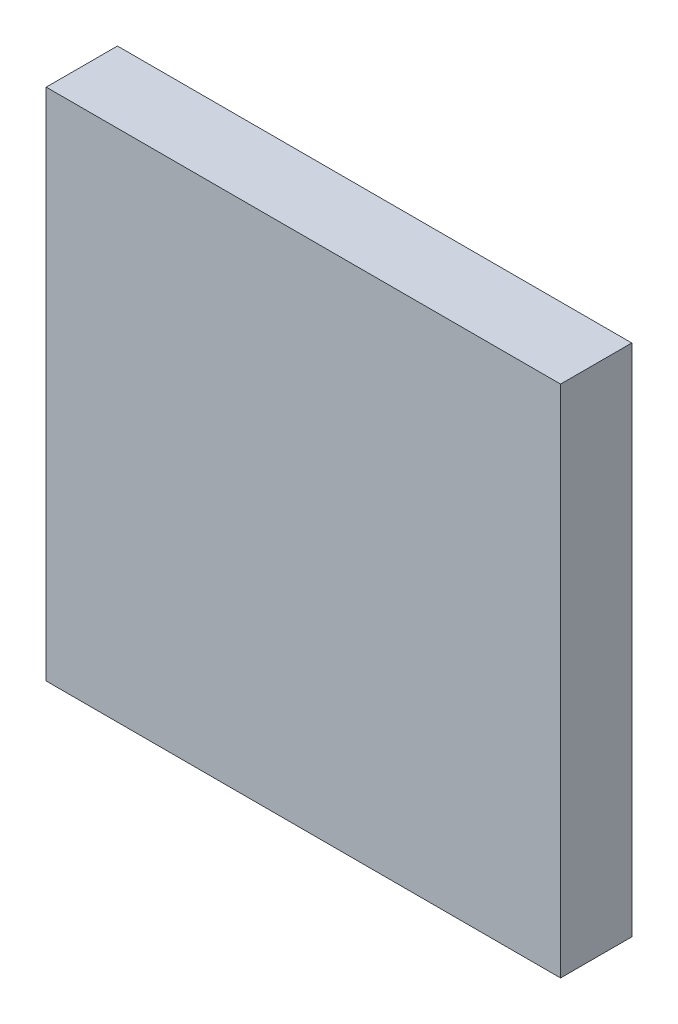
SolidWorks part; units mm, degrees
ref_plane "Front Plane" through (0, 0, 0) normal (0, 0, 1) x (1, 0, 0)
ref_plane "Top Plane" through (0, 0, 0) normal (0, 1, 0) x (1, 0, 0)
ref_plane "Right Plane" through (0, 0, 0) normal (1, 0, 0) x (0, 0, -1)
sketch "Sketch1" plane through (0, 0, 0) normal (0, 0, 1) x (1, 0, 0)
  line L1 (-32.5, -32.5) -> (32.5, -32.5)
  line L2 (-32.5, -32.5) -> (-32.5, 32.5)
  line L3 (-32.5, 32.5) -> (32.5, 32.5)
  line L4 (32.5, -32.5) -> (32.5, 32.5)
  line L5 (-32.5, -32.5) -> (32.5, 32.5) construction
  line L6 (-32.5, 32.5) -> (32.5, -32.5) construction
  point P0 (0, 0)
  dimension "D1" = 65
  dimension "D2" = 65
extrude "Boss-Extrude1" add sketch "Sketch1" along normal blind 9
